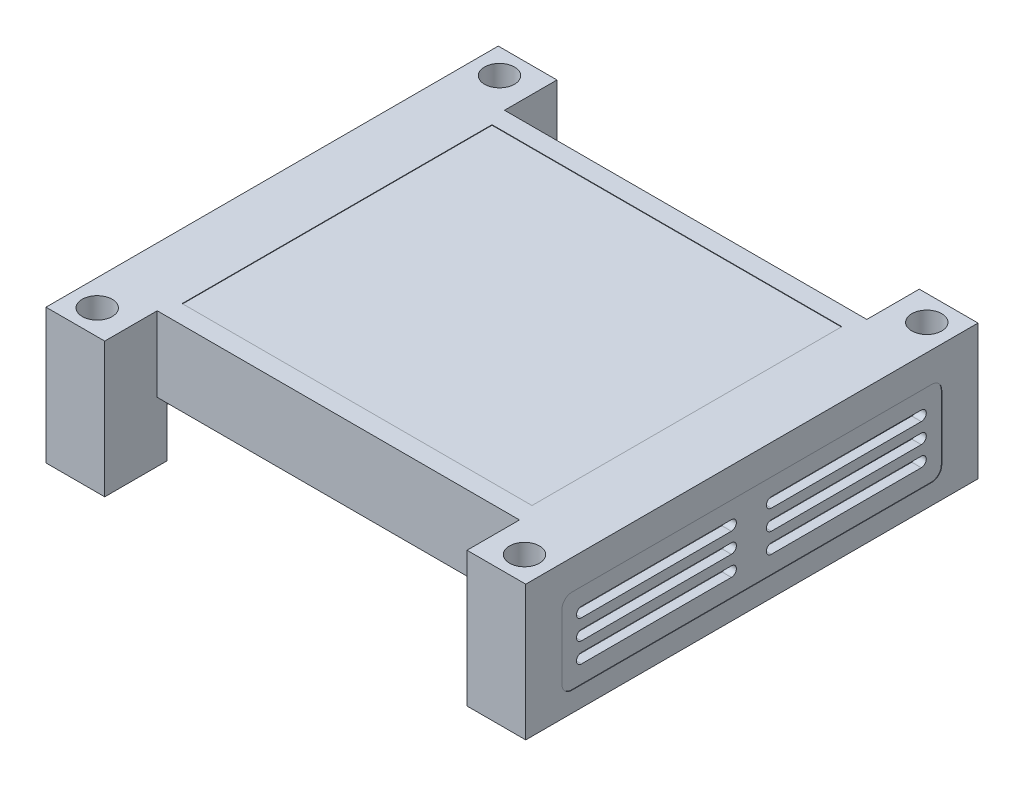
SolidWorks part; units mm, degrees
ref_plane "Front Plane" through (0, 0, 0) normal (0, 0, 1) x (1, 0, 0)
ref_plane "Top Plane" through (0, 0, 0) normal (0, 1, 0) x (1, 0, 0)
ref_plane "Right Plane" through (0, 0, 0) normal (1, 0, 0) x (0, 0, -1)
sketch "Sketch1" plane through (0, 0, 0) normal (0, 1, 0) x (1, 0, 0)
  line L0 (0, 45.25) -> (0, -45.25) construction
  line L1 (-48, 45.25) -> (-36.25, 45.25)
  line L2 (-48, 45.25) -> (-48, -45.25)
  line L3 (-48, -45.25) -> (-36.25, -45.25)
  line L4 (48, 45.25) -> (48, -45.25)
  line L5 (-48, 45.25) -> (48, -45.25) construction
  line L6 (-48, -45.25) -> (48, 45.25) construction
  line L7 (-48, 0) -> (48, 0) construction
  line L8 (-36.25, 45.25) -> (-36.25, 34.75)
  line L9 (-36.25, 34.75) -> (36.25, 34.75)
  line L10 (36.25, 45.25) -> (48, 45.25)
  line L11 (36.25, 45.25) -> (36.25, 34.75)
  line L12 (36.25, -45.25) -> (36.25, -34.75)
  line L13 (-36.25, -34.75) -> (36.25, -34.75)
  line L14 (-36.25, -45.25) -> (-36.25, -34.75)
  line L15 (36.25, -45.25) -> (48, -45.25)
  line L16 (-46, 43.25) -> (-38.25, 43.25)
  line L17 (-38.25, 43.25) -> (-38.25, 32.75)
  line L18 (-38.25, 32.75) -> (38.25, 32.75)
  line L19 (38.25, 43.25) -> (38.25, 32.75)
  line L20 (38.25, 43.25) -> (46, 43.25)
  line L21 (46, 43.25) -> (46, -43.25)
  line L22 (38.25, -43.25) -> (46, -43.25)
  line L23 (38.25, -43.25) -> (38.25, -32.75)
  line L24 (-38.25, -32.75) -> (38.25, -32.75)
  line L25 (-38.25, -43.25) -> (-38.25, -32.75)
  line L26 (-46, -43.25) -> (-38.25, -43.25)
  line L27 (-46, 43.25) -> (-46, -43.25)
  point P0 (0, 0)
  point P14 (0, 34.75)
  point P19 (0, -34.75)
  dimension "D1" = 96
  dimension "D2" = 90.5
  dimension "D3" = 36.25
  dimension "D4" = 10.5
  dimension "D5" = 2
extrude "Boss-Extrude1" add sketch "Sketch1" along normal blind 25
sketch "Sketch2" plane through (0, 25, 0) normal (0, 1, 0) x (1, 0, 0)
  line L12 (36.25, -45.25) -> (48, -45.25)
  line L13 (48, -45.25) -> (48, 45.25)
  line L14 (48, 45.25) -> (36.25, 45.25)
  line L15 (36.25, 45.25) -> (36.25, 34.75)
  line L16 (36.25, 34.75) -> (-36.25, 34.75)
  line L17 (-36.25, 34.75) -> (-36.25, 45.25)
  line L18 (-36.25, 45.25) -> (-48, 45.25)
  line L19 (-48, 45.25) -> (-48, -45.25)
  line L20 (-48, -45.25) -> (-36.25, -45.25)
  line L21 (-36.25, -45.25) -> (-36.25, -34.75)
  line L22 (-36.25, -34.75) -> (36.25, -34.75)
  line L23 (36.25, -34.75) -> (36.25, -45.25)
  line L24 (36.25, -45.25) -> (48, -45.25)
  line L25 (48, -45.25) -> (48, 45.25)
  line L26 (48, 45.25) -> (36.25, 45.25)
  line L27 (36.25, 45.25) -> (36.25, 34.75)
  line L28 (36.25, 34.75) -> (-36.25, 34.75)
  line L29 (-36.25, 34.75) -> (-36.25, 45.25)
  line L30 (-36.25, 45.25) -> (-48, 45.25)
  line L31 (-48, 45.25) -> (-48, -45.25)
  line L32 (-48, -45.25) -> (-36.25, -45.25)
  line L33 (-36.25, -45.25) -> (-36.25, -34.75)
  line L34 (-36.25, -34.75) -> (36.25, -34.75)
  line L35 (36.25, -34.75) -> (36.25, -45.25)
  dimension "D1" = 0
extrude "Boss-Extrude2" add sketch "Sketch2" along normal blind 2
sketch "Sketch3" plane through (0, 0, 34.75) normal (0, 0, 1) x (1, 0, 0)
  line L0 (-36.25, 27) -> (-36.25, 0) construction
  line L1 (-36.25, 12) -> (36.25, 12)
  line L2 (-36.25, 12) -> (-36.25, -6.0582)
  line L3 (-36.25, -6.0582) -> (36.25, -6.0582)
  line L4 (36.25, 12) -> (36.25, -6.0582)
  line L5 (36.25, 27) -> (36.25, 0) construction
  line L6 (-36.25, 27) -> (36.25, 27) construction
  dimension "D1" = 15
extrude "Cut-Extrude1" cut sketch "Sketch3" against normal blind 90
sketch "Sketch4" plane through (0, 27, 0) normal (0, 1, 0) x (1, 0, 0)
  circle A0 centre (-42.75, 40.25) radius 3.5
  circle A1 centre (42.75, 40.25) radius 3.5
  circle A2 centre (42.75, -40.25) radius 3.5
  circle A3 centre (-42.75, -40.25) radius 3.5
extrude "Boss-Extrude9" add sketch "Sketch4" against normal blind 28.5
sketch "Sketch5" plane through (0, -1.5, 0) normal (0, -1, 0) x (1, 0, 0)
  circle A0 centre (-42.75, 40.25) radius 1.5
  circle A1 centre (42.75, 40.25) radius 1.5
  circle A2 centre (42.75, -40.25) radius 1.5
  circle A3 centre (-42.75, -40.25) radius 1.5
extrude "Cut-Extrude2" cut sketch "Sketch5" against normal blind 28.5
sketch "Sketch6" plane through (0, 27, 0) normal (0, 1, 0) x (1, 0, 0)
  line L0 (0, 34.75) -> (0, -34.75) construction
  line L1 (36.25, 34.75) -> (-36.25, 34.75) construction
  line L2 (-36.25, -34.75) -> (36.25, -34.75) construction
  line L3 (-48, 0) -> (48, 0) construction
  line L4 (-48, 45.25) -> (-48, -45.25) construction
  line L5 (48, -45.25) -> (48, 45.25) construction
  circle A0 centre (-42.75, 40.25) radius 3
  circle A1 centre (42.75, 40.25) radius 3
  circle A2 centre (42.75, -40.25) radius 3
  circle A3 centre (-42.75, -40.25) radius 3
extrude "Cut-Extrude3" cut sketch "Sketch6" against normal blind 27
sketch "Sketch7" plane through (0, 27, 0) normal (0, 1, 0) x (1, 0, 0)
  line L0 (0, 34.75) -> (0, -34.75) construction
  line L1 (36.25, 34.75) -> (-36.25, 34.75) construction
  line L2 (-36.25, -34.75) -> (36.25, -34.75) construction
  line L4 (-48, 45.25) -> (-48, -45.25) construction
  line L5 (-48, 0) -> (48, 0) construction
  line L6 (48, -45.25) -> (48, 45.25) construction
  line L7 (-35, 31) -> (35, 31)
  line L8 (-35, 31) -> (-35, -31)
  line L9 (-35, -31) -> (35, -31)
  line L10 (35, 31) -> (35, -31)
  line L11 (-35, 31) -> (35, -31) construction
  line L12 (-35, -31) -> (35, 31) construction
  point P12 (0, 0)
  dimension "D1" = 70
  dimension "D2" = 62
extrude "Cut-Extrude4" cut sketch "Sketch7" against normal blind 0.1
sketch "Sketch8" plane through (-48, 0, 0) normal (-1, 0, 0) x (0, 0, 1)
  line L0 (0, 27) -> (0, 0) construction
  line L1 (-45.25, 27) -> (45.25, 27) construction
  line L3 (-38, 21) -> (38, 21)
  line L4 (-38, 21) -> (-38, 4)
  line L5 (-38, 4) -> (38, 4)
  line L6 (38, 21) -> (38, 4)
  line L7 (-38, 21) -> (38, 4) construction
  line L8 (-38, 4) -> (38, 21) construction
  point P5 (0, 12.5)
  dimension "D1" = 76
  dimension "D2" = 6
  dimension "D3" = 17
extrude "Cut-Extrude5" cut sketch "Sketch8" against normal blind 0.1
fillet "Fillet1" radius 2 4 edges at (-47.95, 4, -38) (-47.95, 4, 38) (-47.95, 21, 38) (-47.95, 21, -38)
sketch "Sketch9" plane through (-47.9, 0, 0) normal (-1, 0, 0) x (0, 0, 1)
  line L0 (0, 21) -> (0, 4) construction
  line L1 (36, 21) -> (-36, 21) construction
  line L2 (-36, 4) -> (36, 4) construction
  line L3 (-38, 12.5) -> (38, 12.5) construction
  line L4 (-38, 19) -> (-38, 6) construction
  line L5 (38, 6) -> (38, 19) construction
  line L6 (-34, 12.5) -> (-4, 12.5) construction
  line L7 (-34, 13.5) -> (-4, 13.5)
  line L8 (-34, 11.5) -> (-4, 11.5)
  line L9 (-34, 16.5) -> (-4, 16.5) construction
  line L10 (-34, 17.5) -> (-4, 17.5)
  line L11 (-34, 15.5) -> (-4, 15.5)
  line L12 (-34, 8.5) -> (-4, 8.5) construction
  line L13 (-34, 9.5) -> (-4, 9.5)
  line L14 (-34, 7.5) -> (-4, 7.5)
  line L15 (-34, 8.5) -> (-4, 8.5) construction
  line L16 (-34, 7.5) -> (-4, 7.5)
  line L17 (-34, 9.5) -> (-4, 9.5)
  line L18 (-34, 16.5) -> (-4, 16.5) construction
  line L19 (-34, 15.5) -> (-4, 15.5)
  line L20 (-34, 17.5) -> (-4, 17.5)
  line L21 (-34, 8.5) -> (-4, 8.5) construction
  line L22 (-34, 7.5) -> (-4, 7.5)
  line L23 (-34, 9.5) -> (-4, 9.5)
  line L24 (-34, 16.5) -> (-4, 16.5) construction
  line L25 (-34, 15.5) -> (-4, 15.5)
  line L26 (-34, 17.5) -> (-4, 17.5)
  line L27 (-34, 16.5) -> (-4, 16.5) construction
  line L28 (-34, 17.5) -> (-4, 17.5)
  line L29 (-34, 15.5) -> (-4, 15.5)
  line L30 (-34, 8.5) -> (-4, 8.5) construction
  line L31 (-34, 9.5) -> (-4, 9.5)
  line L32 (-34, 7.5) -> (-4, 7.5)
  line L33 (34, 8.5) -> (4, 8.5) construction
  line L34 (34, 9.5) -> (4, 9.5)
  line L35 (34, 7.5) -> (4, 7.5)
  line L36 (34, 12.5) -> (4, 12.5) construction
  line L37 (34, 13.5) -> (4, 13.5)
  line L38 (34, 11.5) -> (4, 11.5)
  line L39 (34, 16.5) -> (4, 16.5) construction
  line L40 (34, 17.5) -> (4, 17.5)
  line L41 (34, 15.5) -> (4, 15.5)
  arc A0 (-34, 13.5) -> (-34, 11.5) centre (-34, 12.5) ccw
  arc A1 (-4, 11.5) -> (-4, 13.5) centre (-4, 12.5) ccw
  arc A2 (-34, 17.5) -> (-34, 15.5) centre (-34, 16.5) ccw
  arc A3 (-4, 15.5) -> (-4, 17.5) centre (-4, 16.5) ccw
  arc A4 (-34, 9.5) -> (-34, 7.5) centre (-34, 8.5) ccw
  arc A5 (-4, 7.5) -> (-4, 9.5) centre (-4, 8.5) ccw
  arc A6 (-34, 7.5) -> (-34, 9.5) centre (-34, 8.5) cw
  arc A7 (-4, 9.5) -> (-4, 7.5) centre (-4, 8.5) cw
  arc A8 (-34, 15.5) -> (-34, 17.5) centre (-34, 16.5) cw
  arc A9 (-4, 17.5) -> (-4, 15.5) centre (-4, 16.5) cw
  arc A10 (-34, 7.5) -> (-34, 9.5) centre (-34, 8.5) cw
  arc A11 (-4, 9.5) -> (-4, 7.5) centre (-4, 8.5) cw
  arc A12 (-34, 15.5) -> (-34, 17.5) centre (-34, 16.5) cw
  arc A13 (-4, 17.5) -> (-4, 15.5) centre (-4, 16.5) cw
  arc A14 (-34, 17.5) -> (-34, 15.5) centre (-34, 16.5) ccw
  arc A15 (-4, 15.5) -> (-4, 17.5) centre (-4, 16.5) ccw
  arc A16 (-34, 9.5) -> (-34, 7.5) centre (-34, 8.5) ccw
  arc A17 (-4, 7.5) -> (-4, 9.5) centre (-4, 8.5) ccw
  arc A18 (34, 9.5) -> (34, 7.5) centre (34, 8.5) cw
  arc A19 (4, 7.5) -> (4, 9.5) centre (4, 8.5) cw
  arc A20 (34, 13.5) -> (34, 11.5) centre (34, 12.5) cw
  arc A21 (4, 11.5) -> (4, 13.5) centre (4, 12.5) cw
  arc A22 (34, 17.5) -> (34, 15.5) centre (34, 16.5) cw
  arc A23 (4, 15.5) -> (4, 17.5) centre (4, 16.5) cw
  point P14 (-19, 12.5)
  point P23 (-19, 16.5)
  point P29 (-19, 8.5)
  point P71 (19, 8.5)
  point P78 (19, 12.5)
  point P85 (19, 16.5)
  dimension "D1" = 30
  dimension "D2" = 4
  dimension "D3" = 2
  dimension "D4" = 2
  dimension "D5" = 2
extrude "Cut-Extrude6" cut sketch "Sketch9" against normal blind 5 contours L11 A3 L10 A2 | L7 A1 L8 A0 | L13 A5 L14 A4 | L40 A23 L41 A22 | L37 A21 L38 A20 | L34 A19 L35 A18
mirror "Mirror1" about plane through (0, 0, 0) normal (1, 0, 0) of "Cut-Extrude6", "Fillet1", "Cut-Extrude5"
